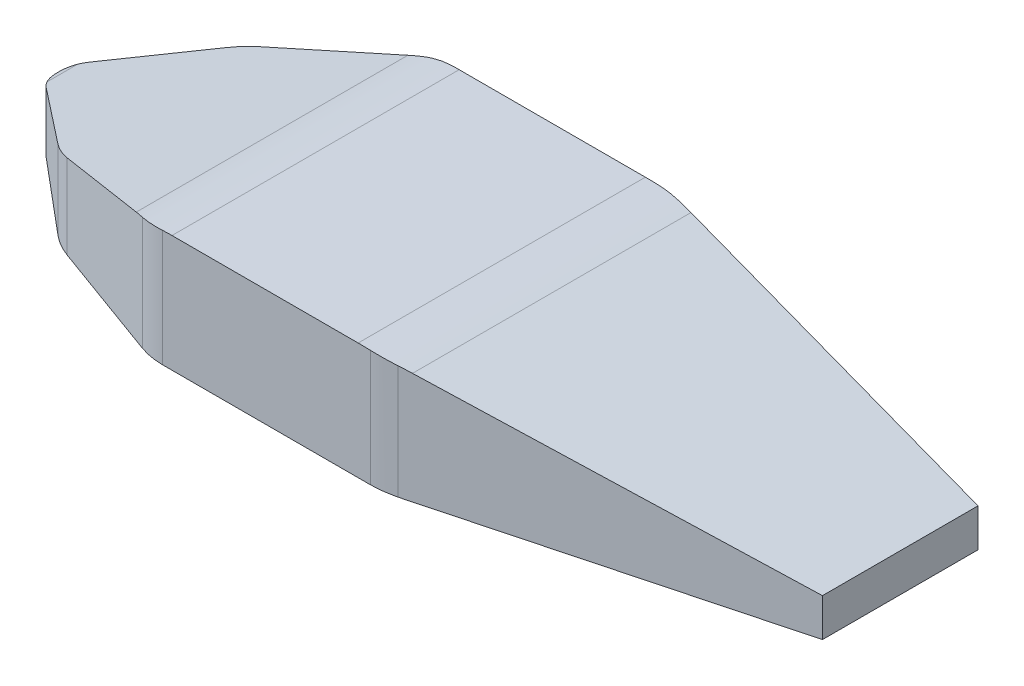
SolidWorks part; units mm, degrees
ref_plane "Front Plane" through (0, 0, 0) normal (0, 0, 1) x (1, 0, 0)
ref_plane "Top Plane" through (0, 0, 0) normal (0, 1, 0) x (1, 0, 0)
ref_plane "Right Plane" through (0, 0, 0) normal (1, 0, 0) x (0, 0, -1)
sketch "Sketch1" plane through (0, 0, 0) normal (0, 1, 0) x (1, 0, 0)
  line L0 (146.0698, 122.5671) -> (556.1483, 466.6637)
  line L1 (676.4552, 536.1229) -> (1335.1737, 775.877)
  line L2 (1471.9818, 800) -> (2631.4601, 800)
  line L3 (2770.3786, 787.8462) -> (4781.451, 433.24)
  line L4 (4781.451, 433.24) -> (4781.451, -433.24)
  line L5 (4781.451, -433.24) -> (2770.3786, -787.8462)
  line L6 (2631.4601, -800) -> (1471.9818, -800)
  line L7 (1335.1737, -775.877) -> (676.4552, -536.1229)
  line L8 (556.1483, -466.6637) -> (146.0698, -122.5671)
  arc A0 (146.0698, 122.5671) -> (146.0698, -122.5671) centre (248.9159, 0) ccw
  arc A1 (676.4552, -536.1229) -> (556.1483, -466.6637) centre (813.2633, -160.2459) cw
  arc A2 (1471.9818, -800) -> (1335.1737, -775.877) centre (1471.9818, -400) cw
  arc A3 (1335.1737, 775.877) -> (1471.9818, 800) centre (1471.9818, 400) cw
  arc A4 (556.1483, 466.6637) -> (676.4552, 536.1229) centre (813.2633, 160.2459) cw
  arc A5 (2770.3786, -787.8462) -> (2631.4601, -800) centre (2631.4601, 0) cw
  arc A6 (2631.4601, 800) -> (2770.3786, 787.8462) centre (2631.4601, 0) cw
  point P12 (0, 0)
  point P15 (610.178, -512)
  point P18 (1401.451, -800)
  point P21 (1401.451, 800)
  point P24 (610.178, 512)
  point P27 (2701.451, -800)
  point P30 (2701.451, 800)
  dimension "r0" = 160
  dimension "r1" = 400
  dimension "r3" = 800
  dimension "x1" = 610.178
  dimension "x2" = 1401.451
  dimension "x3" = 2701.451
  dimension "x4" = 4781.451
  dimension "x6" = 2701.451
  dimension "x7" = 1401.451
  dimension "x8" = 610.178
  dimension "y1" = 512
  dimension "y2" = 800
  dimension "y4" = 433.24
  dimension "y5" = 433.24
  dimension "y6" = 800
  dimension "y8" = 512
extrude "TopView_Extrude" add sketch "Sketch1" along normal blind 800
sketch "Sketch2" plane through (0, 0, 0) normal (0, 0, 1) x (1, 0, 0)
  line L0 (0, 300) -> (0, 332.8541)
  line L1 (113.6551, 478.3844) -> (1282.1337, 770.2016)
  line L2 (1524.433, 800) -> (2561.5973, 800)
  line L3 (2839.9436, 780.5361) -> (4781.451, 507.675)
  line L4 (4781.451, 507.675) -> (4781.451, 295.448)
  line L5 (4781.451, 295.448) -> (2805.9583, 157.3079)
  line L6 (2596.6885, 150) -> (150, 150)
  arc A0 (0, 332.8541) -> (113.6551, 478.3844) centre (150, 332.8541) cw
  arc A1 (0, 300) -> (150, 150) centre (150, 300) ccw
  arc A2 (1282.1337, 770.2016) -> (1524.433, 800) centre (1524.433, -200) cw
  arc A3 (2561.5973, 800) -> (2839.9436, 780.5361) centre (2561.5973, -1200) cw
  arc A4 (2805.9583, 157.3079) -> (2596.6885, 150) centre (2596.6885, 3150) cw
  point P10 (0, 450)
  point P13 (0, 150)
  point P16 (1401.451, 800)
  point P19 (2701.451, 800)
  point P22 (2701.451, 150)
  dimension "r0" = 150
  dimension "r2" = 1000
  dimension "r3" = 2000
  dimension "r6" = 3000
  dimension "x2" = 1401.451
  dimension "x3" = 2701.451
  dimension "x4" = 4781.451
  dimension "x6" = 2701.451
  dimension "y0" = 150
  dimension "y1" = 450
  dimension "y2" = 800
  dimension "y4" = 507.675
  dimension "y5" = 295.448
extrude "SideProfile_Cut" cut sketch "Sketch2" against normal through all and the other way through all flip side to cut
